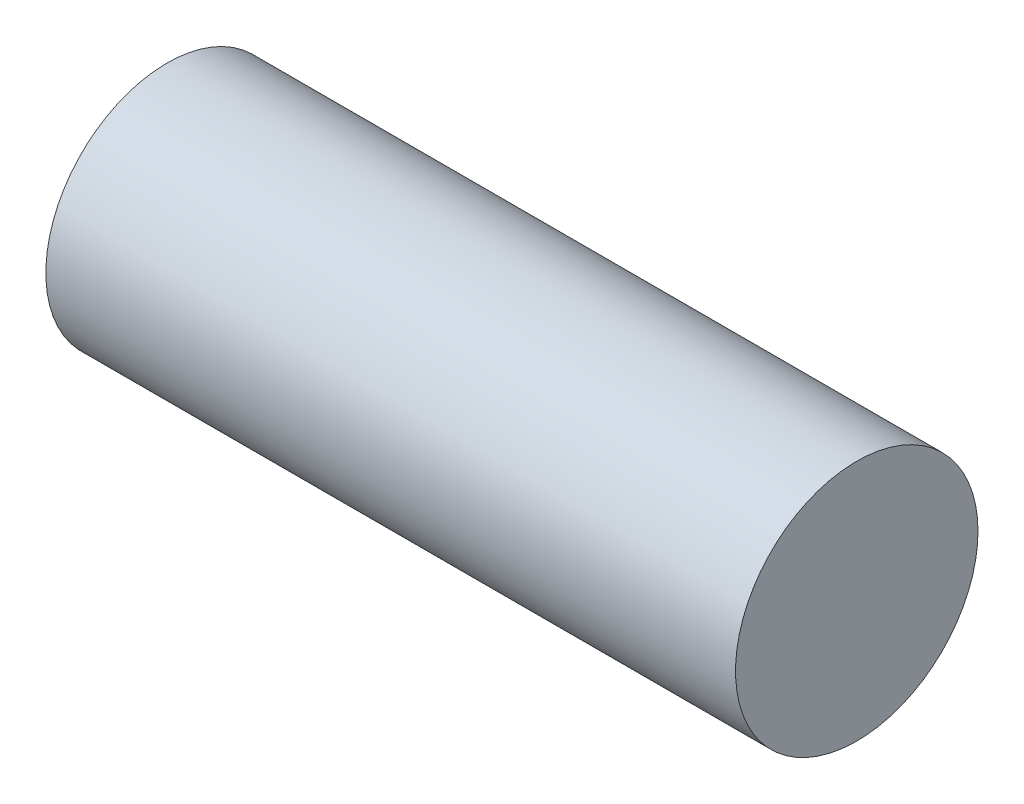
SolidWorks part; units mm, degrees
ref_plane "前视基准面" through (0, 0, 0) normal (0, 0, 1) x (1, 0, 0)
ref_plane "上视基准面" through (0, 0, 0) normal (0, 1, 0) x (1, 0, 0)
ref_plane "右视基准面" through (0, 0, 0) normal (1, 0, 0) x (0, 0, -1)
sketch "草图1" plane through (0, 0, 0) normal (1, 0, 0) x (0, 0, -1)
  circle A0 centre (-38.4674, 25.1675) radius 4.5
extrude "凸台-拉伸1" add sketch "草图1" along normal blind 25.6
